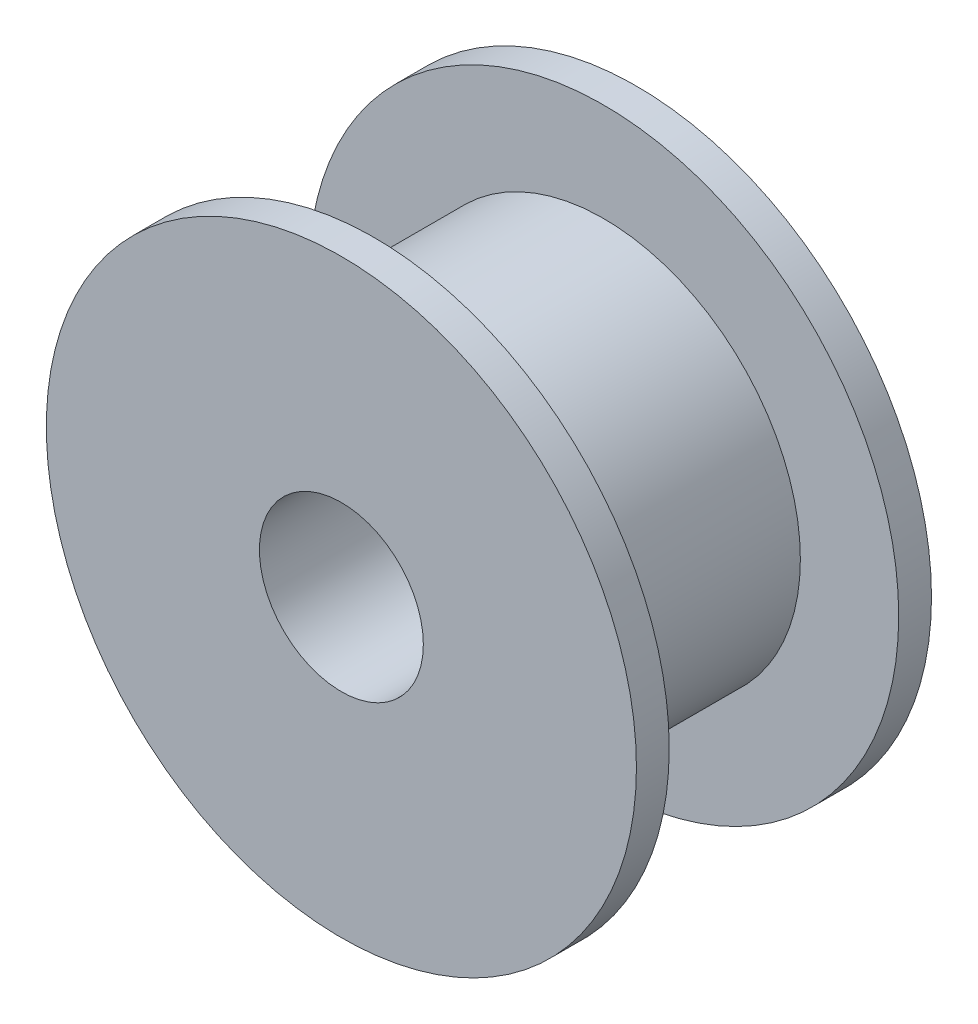
SolidWorks part; units mm, degrees
ref_plane "Front Plane" through (0, 0, 0) normal (0, 0, 1) x (1, 0, 0)
ref_plane "Top Plane" through (0, 0, 0) normal (0, 1, 0) x (1, 0, 0)
ref_plane "Right Plane" through (0, 0, 0) normal (1, 0, 0) x (0, 0, -1)
sketch "Sketch1" plane through (0, 0, 0) normal (0, 0, 1) x (1, 0, 0)
  circle A0 centre (0, 0) radius 9
  dimension "D1" = 18
extrude "Boss-Extrude1" add sketch "Sketch1" along normal blind 1
sketch "Sketch2" plane through (0, 0, 1) normal (0, 0, 1) x (1, 0, 0)
  circle A0 centre (0, 0) radius 6
  dimension "D1" = 12
extrude "Boss-Extrude2" add sketch "Sketch2" along normal blind 7
sketch "Sketch3" plane through (0, 0, 8) normal (0, 0, 1) x (1, 0, 0)
  circle A0 centre (0, 0) radius 9
  dimension "D1" = 18
extrude "Boss-Extrude3" add sketch "Sketch3" along normal blind 1
sketch "Sketch4" plane through (0, 0, 9) normal (0, 0, 1) x (1, 0, 0)
  circle A0 centre (0, 0) radius 2.5
  dimension "D1" = 5
extrude "Cut-Extrude1" cut sketch "Sketch4" against normal through all
